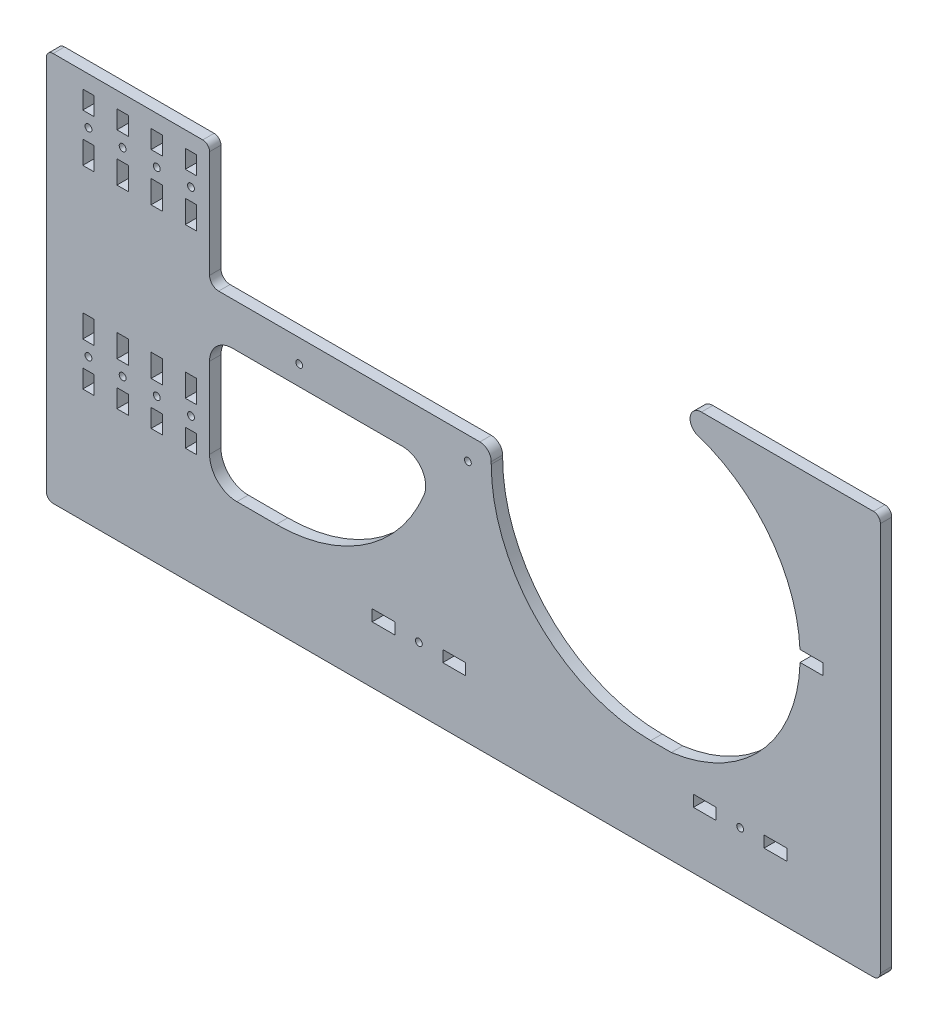
SolidWorks part; units mm, degrees
ref_plane "Plano frontal" through (0, 0, 0) normal (0, 0, 1) x (1, 0, 0)
ref_plane "Plano superior" through (0, 0, 0) normal (0, 1, 0) x (1, 0, 0)
ref_plane "Plano direito" through (0, 0, 0) normal (1, 0, 0) x (0, 0, -1)
sketch "Model" plane through (0, 0, 0) normal (0, 0, 1) x (1, 0, 0)
  line L0 (-319, 38) -> (-319, 46)
  line L1 (-319, 46) -> (-324, 46)
  line L2 (-324, 46) -> (-324, 38)
  line L3 (-324, 38) -> (-319, 38)
  line L4 (-323.9999, 151.9999) -> (-323.9999, 143.9999)
  line L5 (-323.9999, 143.9999) -> (-318.9999, 143.9999)
  line L6 (-318.9999, 143.9999) -> (-318.9999, 151.9999)
  line L7 (-318.9999, 151.9999) -> (-323.9999, 151.9999)
  line L8 (-303.9999, 143.9999) -> (-303.9999, 151.9999)
  line L9 (-303.9999, 151.9999) -> (-308.9999, 151.9999)
  line L10 (-308.9999, 151.9999) -> (-308.9999, 143.9999)
  line L11 (-308.9999, 143.9999) -> (-303.9999, 143.9999)
  line L12 (-334, 57) -> (-334, 67)
  line L13 (-334, 67) -> (-339, 67)
  line L14 (-339, 67) -> (-339, 57)
  line L15 (-339, 57) -> (-334, 57)
  line L16 (-334, 38) -> (-334, 46)
  line L17 (-334, 46) -> (-339, 46)
  line L18 (-339, 46) -> (-339, 38)
  line L19 (-339, 38) -> (-334, 38)
  line L20 (-319, 57) -> (-319, 67)
  line L21 (-319, 67) -> (-324, 67)
  line L22 (-324, 67) -> (-324, 57)
  line L23 (-324, 57) -> (-319, 57)
  line L24 (-333.9999, 143.9999) -> (-333.9999, 151.9999)
  line L25 (-333.9999, 151.9999) -> (-338.9999, 151.9999)
  line L26 (-338.9999, 151.9999) -> (-338.9999, 143.9999)
  line L27 (-338.9999, 143.9999) -> (-333.9999, 143.9999)
  line L28 (-309, 57) -> (-304, 57)
  line L29 (-304, 57) -> (-304, 67)
  line L30 (-304, 67) -> (-309, 67)
  line L31 (-309, 67) -> (-309, 57)
  line L32 (-309, 46) -> (-309, 38)
  line L33 (-309, 38) -> (-304, 38)
  line L34 (-304, 38) -> (-304, 46)
  line L35 (-304, 46) -> (-309, 46)
  line L36 (-318.9999, 133) -> (-323.9999, 133)
  line L37 (-323.9999, 133) -> (-323.9999, 123)
  line L38 (-323.9999, 123) -> (-318.9999, 123)
  line L39 (-318.9999, 123) -> (-318.9999, 133)
  line L40 (-333.9999, 133) -> (-338.9999, 133)
  line L41 (-338.9999, 133) -> (-338.9999, 123)
  line L42 (-338.9999, 123) -> (-333.9999, 123)
  line L43 (-333.9999, 123) -> (-333.9999, 133)
  line L44 (-303.9999, 133) -> (-308.9999, 133)
  line L45 (-308.9999, 133) -> (-308.9999, 123)
  line L46 (-308.9999, 123) -> (-303.9999, 123)
  line L47 (-303.9999, 123) -> (-303.9999, 133)
  line L48 (-288.9999, 151.9999) -> (-293.9999, 151.9999)
  line L49 (-293.9999, 151.9999) -> (-293.9999, 143.9999)
  line L50 (-293.9999, 143.9999) -> (-288.9999, 143.9999)
  line L51 (-288.9999, 143.9999) -> (-288.9999, 151.9999)
  line L52 (-288.9999, 133) -> (-293.9999, 133)
  line L53 (-293.9999, 133) -> (-293.9999, 123)
  line L54 (-293.9999, 123) -> (-288.9999, 123)
  line L55 (-288.9999, 123) -> (-288.9999, 133)
  line L56 (-288.9999, 46) -> (-293.9999, 46)
  line L57 (-293.9999, 46) -> (-293.9999, 38)
  line L58 (-293.9999, 38) -> (-288.9999, 38)
  line L59 (-288.9999, 38) -> (-288.9999, 46)
  line L60 (-288.9999, 66.9999) -> (-293.9999, 66.9999)
  line L61 (-293.9999, 66.9999) -> (-293.9999, 57)
  line L62 (-293.9999, 57) -> (-288.9999, 57)
  line L63 (-288.9999, 57) -> (-288.9999, 66.9999)
  line L64 (8, -12) -> (-351.8933, -12)
  line L65 (-354.9999, -9.0019) -> (-354.9999, 156.0055)
  line L66 (-351.9999, 159.0055) -> (-286.3549, 159.0055)
  line L67 (-283.3549, 156.0055) -> (-283.3549, 109.0327)
  line L68 (-279.3549, 105.0327) -> (-240.2649, 105.0327)
  line L69 (-240.2649, 105.0327) -> (-174.7267, 105.0327)
  line L70 (-174.7267, 105.0327) -> (-164.7355, 105.0327)
  line L71 (-159.7355, 100.0327) -> (-159.7355, 99)
  line L72 (-89.7355, 29) -> (-80.698, 29)
  line L73 (-24.2117, 91.4794) -> (-14.2203, 91.4794)
  line L74 (-14.2203, 91.4794) -> (-14.2203, 96.3794)
  line L75 (-14.2203, 96.3794) -> (-24.2483, 96.3794)
  line L76 (-67.4958, 165) -> (8.0068, 165)
  line L77 (11, 161.7975) -> (11, -9)
  line L78 (-283.3549, 76.3516) -> (-283.3549, 41)
  line L79 (-271.3549, 29) -> (-254.0589, 29)
  line L80 (-198.5223, 86.3516) -> (-273.3549, 86.3516)
  line L81 (-61, 13) -> (-61, 18)
  line L82 (-61, 18) -> (-71, 18)
  line L83 (-71, 18) -> (-71, 13)
  line L84 (-71, 13) -> (-61, 13)
  line L85 (-30.0041, 13) -> (-30.0041, 18)
  line L86 (-30.0041, 18) -> (-40.0041, 18)
  line L87 (-40.0041, 18) -> (-40.0041, 13)
  line L88 (-40.0041, 13) -> (-30.0041, 13)
  line L89 (-212, 18) -> (-212, 13)
  line L90 (-212, 13) -> (-202, 13)
  line L91 (-202, 13) -> (-202, 18)
  line L92 (-202, 18) -> (-212, 18)
  line L93 (-181.0041, 18) -> (-181.0041, 13)
  line L94 (-181.0041, 13) -> (-171.0041, 13)
  line L95 (-171.0041, 13) -> (-171.0041, 18)
  line L96 (-171.0041, 18) -> (-181.0041, 18)
  circle A0 centre (-291.5, 51.5) radius 1.5
  circle A1 centre (-291.5, 138.5) radius 1.5
  circle A2 centre (-306.5, 138.5) radius 1.5
  circle A3 centre (-336.4999, 51.4894) radius 1.5
  circle A4 centre (-306.5, 51.5) radius 1.5
  circle A5 centre (-336.5, 138.5) radius 1.5
  circle A6 centre (-321.5, 138.5) radius 1.5
  circle A7 centre (-321.5, 51.5) radius 1.5
  circle A8 centre (-50.5, 15.5) radius 1.5
  circle A9 centre (-170, 95) radius 1.5
  circle A10 centre (-244, 95) radius 1.5
  circle A11 centre (-191.5, 15.5) radius 1.5
  arc A12 (-354.9999, -9.0019) -> (-351.8933, -12) centre (-351.9999, -9.0019) ccw
  arc A13 (-351.9999, 159.0055) -> (-354.9999, 156.0055) centre (-351.9999, 156.0055) ccw
  arc A14 (-283.3549, 156.0055) -> (-286.3549, 159.0055) centre (-286.3549, 156.0055) ccw
  arc A15 (-283.3549, 109.0327) -> (-279.3549, 105.0327) centre (-279.3549, 109.0327) ccw
  arc A16 (-159.7355, 100.0327) -> (-164.7355, 105.0327) centre (-164.7355, 100.0327) ccw
  arc A17 (-159.7355, 99) -> (-89.7355, 29) centre (-89.7355, 99) ccw
  arc A18 (-80.698, 29) -> (-24.2117, 91.4794) centre (-89.182, 93.4439) ccw
  arc A19 (-24.2483, 96.3794) -> (-69.0448, 155.246) centre (-89.182, 93.4439) ccw
  arc A20 (-67.4958, 165) -> (-69.0448, 155.246) centre (-67.4958, 160) ccw
  arc A21 (11, 161.7975) -> (8.0068, 165) centre (8.0068, 162) ccw
  arc A22 (8, -12) -> (11, -9) centre (8, -9) ccw
  arc A23 (-283.3549, 41) -> (-271.3549, 29) centre (-271.3549, 41) ccw
  arc A24 (-254.0589, 29) -> (-189.2374, 72.577) centre (-254.0589, 99) ccw
  arc A25 (-189.2374, 72.577) -> (-198.5223, 86.3516) centre (-198.4977, 76.3517) ccw
  arc A26 (-273.3549, 86.3516) -> (-283.3549, 76.3516) centre (-273.3549, 76.3516) ccw
extrude "Ressalto-extrusão1" add sketch "Model" along normal blind 5
